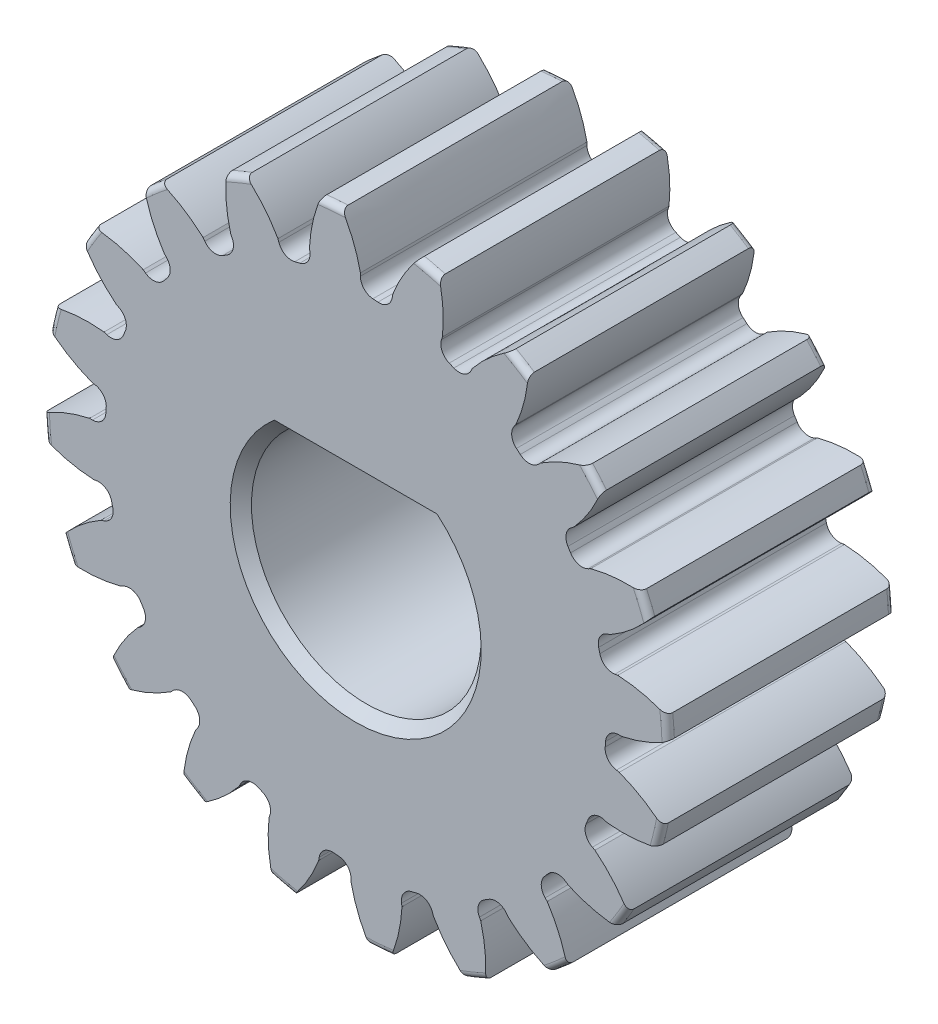
SolidWorks part; units mm, degrees
material "ABS"
ref_plane "Front" through (0, 0, 0) normal (0, 0, 1) x (1, 0, 0)
ref_plane "Top" through (0, 0, 0) normal (0, 1, 0) x (1, 0, 0)
ref_plane "Right" through (0, 0, 0) normal (1, 0, 0) x (0, 0, -1)
sketch "Sketch1" plane through (0, 0, 0) normal (0, 0, 1) x (1, 0, 0)
  line L0 (-254, 0) -> (254, 0) construction
  circle A0 centre (0, 0) radius 8.763
  circle A1 centre (0, 0) radius 7.9375 construction
  circle A3 centre (0, 0) radius 7.0191 construction
  dimension "D1" = 0.9184
  dimension "D2" = 1.7439
  dimension "D3" = 0.8255
extrude "Boss-Extrude1" add sketch "Sketch1" against normal blind 6.35
sketch "Sketch2" plane through (0, 0, 0) normal (1, 0, 0) x (0, 0, -1)
  line L0 (4.7625, 0) -> (11.1252, 0)
  line L1 (4.7625, 0) -> (4.7625, 5.9531)
  line L2 (4.7625, 5.9531) -> (11.1252, 5.9531)
  line L3 (11.1252, 5.9531) -> (11.1252, 0)
  point P5 (11.1252, -5.9531)
  point P6 (0, -8.763)
  point P7 (6.35, -8.763)
  point P9 (0, 8.763)
revolve "Revolve1" add sketch "Sketch2" angle 360 mid plane about L0
fillet "Fillet2" radius 0.1753 3 edges at (8.763, 0, -6.35) (8.763, 0, 0) (5.9531, 0, -6.35)
sketch "Sketch3" plane through (0, 0, 0) normal (0, 0, 1) x (1, 0, 0)
  line L0 (0, 0) -> (0, 8.763) construction
  line L1 (-2.5511, 7.009) -> (0, 7.9375)
  line L2 (-9.5921, 7.9375) -> (9.5921, 7.9375) construction
  line L3 (-9.0136, 4.6568) -> (9.0136, 11.2182) construction
  line L4 (-2.5511, 7.009) -> (0, 0) construction
  line L5 (-6.2194, 4.1174) -> (0, 0) construction
  line L6 (-6.2194, 4.1174) -> (-2.0982, 10.3425) construction
  line L7 (-1.7721, 7.2452) -> (0, 0) construction
  line L8 (-1.7721, 7.2452) -> (0.0739, 7.6967) construction
  arc A0 (-2.5511, 7.009) -> (-6.2194, 4.1174) centre (0, 0) ccw
  circle A1 centre (0, 0) radius 7.9375 construction
  circle A2 centre (0, 0) radius 7.4588 construction
  arc A3 (-2.5511, 7.009) -> (-1.7721, 7.2452) centre (0, 0) cw
  circle A4 centre (0, 0) radius 8.763 construction
  point P6 (0, 7.9375)
  dimension "D1" = 2.7148
  dimension "D3" = 7.4657
  dimension "D5" = 1.9003
  dimension "D2" = 4.7509
  dimension "D4" = 0.8144
sketch "Sketch4" plane through (0, 0, 0) normal (0, 0, 1) x (1, 0, 0)
  line L0 (0, 0) -> (0.6209, 7.8886) construction
  line L1 (0.1318, 7.4576) -> (0.1318, 7.0179)
  line L2 (0, 7.9375) -> (1.2417, 7.8398) construction
  line L3 (1.0365, 7.3864) -> (0.9677, 6.9521)
  line L4 (0.1318, 7.0179) -> (0, 0) construction
  line L5 (0, 0) -> (0, 8.763) construction
  line L6 (-6.2194, 4.1174) -> (-2.0982, 10.3425) construction
  line L7 (-6.2194, 4.1174) -> (-2.0982, 10.3425) construction
  arc A0 (0.9677, 6.9521) -> (0.1318, 7.0179) centre (0, 0) ccw
  arc A1 (0, 7.9375) -> (1.2417, 7.8398) centre (0, 0) cw construction
  circle A2 centre (0, 0) radius 7.9375 construction
  circle A3 centre (0, 0) radius 7.4588 construction
  circle A4 centre (0, 0) radius 7.0191 construction
  arc A5 (3.6903, 9.8869) -> (-2.0982, 10.3425) centre (0, 0) ccw
  spline S0 degree 2 poles (-2.0982, 10.3425) (-0.2509, 9.2652) (0.1318, 7.4576) knots 0 0 0 1 1 1
  spline S1 degree 2 poles (3.6903, 9.8869) (1.6972, 9.1118) (1.0365, 7.3864) knots 0 0 0 1 1 1
  dimension "D1" = 1.2468
extrude "Cut-Extrude1" cut sketch "Sketch4" against normal through all
fillet "Fillet1" radius 0.374 2 edges at (0.9677, 6.9521, -3.175) (0.1318, 7.0179, -3.175)
pattern_circular "CirPattern1" count 20 over 360 about axis through (0, 0, -6.35) along (0, 0, 1) of "Cut-Extrude1", "Fillet1"
sketch "Sketch5" plane through (0, 0, 0) normal (0, 0, 1) x (1, 0, 0)
  line L0 (-2.1667, 2.3813) -> (2.1667, 2.3813)
  line L1 (0, -3.2195) -> (0, 2.3813) construction
  circle A0 centre (0, 0) radius 3.2195
  dimension "D1" = 5.6007
  dimension "D2" = 6.4389
extrude "Cut-Extrude2" cut sketch "Sketch5" against normal through all contours A0 L1 L0 | L1 A0 L0
chamfer "Chamfer1" distance 0.2977 angle 45 4 edges at (5.9531, 0, -11.1252) (0, -3.2195, 0) (0, -3.2194, -11.1252) (0, 2.3813, 0)
sketch "Pitch Dia" plane through (0, 0, 0) normal (0, 0, 1) x (1, 0, 0)
  circle A0 centre (0, 0) radius 7.9375 construction
  circle A1 centre (0, 0) radius 7.9375 construction
sketch "Sketch6" plane through (0, 0, -11.1252) normal (0, 0, -1) x (-1, 0, 0)
  circle A0 centre (0, 0) radius 6.35
  dimension "D1" = 12.7
extrude "Cut-Extrude3" cut sketch "Sketch6" against normal blind 4.7752
equation "\"D1@Boss-Extrude1\"=\"Face Wd@Sketch2\"+.0625"
equation "\"D2@Sketch3\" = \"D1@Sketch3\"*1.75"
equation "\"D3@Sketch3\" = \"D1@Sketch3\"+\"D2@Sketch3\""
equation "\"D4@Sketch3\" = \"D1@Sketch3\"*.3"
equation "\"D5@Sketch3\" = \"D1@Sketch3\"-\"D4@Sketch3\""
equation "\"D1@Sketch4\" = 1.5708/(\"Number of Teeth@Sketch1\"/\"Ptich Dia@Sketch1\")"
equation "\"D1@Chamfer1\" = \"B Hub Dia@Sketch2\"*.025"
equation "\"D1@CirPattern1\" = \"Number of Teeth@Sketch1\""
equation "\"D1@Fillet1\" = \"D1@Sketch4\"*.3"
equation "\"D1@Fillet2\" = \"OD@Sketch1\"*.01"
equation "\"D1@Sketch1\" = 1.157/(\"Number of Teeth@Sketch1\"/\"Ptich Dia@Sketch1\")"
